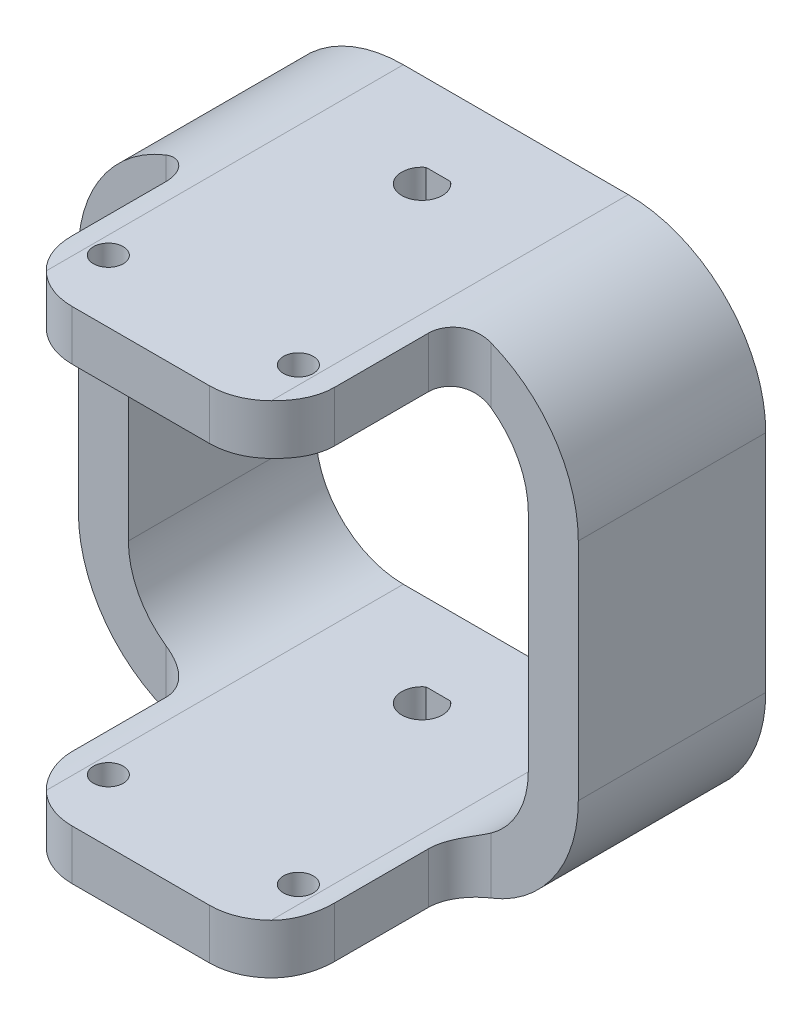
SolidWorks part; units mm, degrees
material "Plastique personnalisé"
ref_plane "Plan de face" through (0, 0, 0) normal (0, 0, 1) x (1, 0, 0)
ref_plane "Plan de dessus" through (0, 0, 0) normal (0, 1, 0) x (1, 0, 0)
ref_plane "Plan de droite" through (0, 0, 0) normal (1, 0, 0) x (0, 0, -1)
sketch "Esquisse1" plane through (0, 0, 0) normal (0, 0, 1) x (1, 0, 0)
  line L1 (40, -40) -> (-40, -40)
  line L2 (40, -40) -> (40, 40)
  line L3 (40, 40) -> (-40, 40)
  line L4 (-40, -40) -> (-40, 40)
  line L5 (40, -40) -> (-40, 40) construction
  line L6 (40, 40) -> (-40, -40) construction
  line L7 (-32, -32) -> (32, -32)
  line L8 (-32, -32) -> (-32, 32)
  line L9 (-32, 32) -> (32, 32)
  line L10 (32, -32) -> (32, 32)
  line L11 (-32, -32) -> (32, 32) construction
  line L12 (-32, 32) -> (32, -32) construction
  point P0 (0, 0)
  point P11 (0, 0)
  dimension "D1" = 8
  dimension "D3" = 80
extrude "Boss.-Extru.1" add sketch "Esquisse1" along normal mid plane 30
sketch "Esquisse2" plane through (0, 0, 0) normal (1, 0, 0) x (0, 0, -1)
  circle A0 centre (0, 0) radius 5
  dimension "D1" = 10
extrude "Enlèv. mat.-Extru.1" [suppressed] cut sketch "Esquisse2" against normal through all both and the other way through all
sketch "Esquisse3" plane through (0, -40, 0) normal (0, -1, 0) x (-1, 0, 0)
  circle A0 centre (0, 0) radius 5
  dimension "D1" = 10
extrude "Boss.-Extru.2" [suppressed] add sketch "Esquisse3" along normal blind 20
mirror "Symétrie1" [suppressed] about plane through (0, 0, 0) normal (0, 1, 0)
sketch "Esquisse7" plane through (0, 0, 15) normal (0, 0, 1) x (1, 0, 0)
  line L0 (40, 40) -> (-40, 40) construction
  line L1 (21, 32) -> (-21, 32)
  line L2 (21, 32) -> (21, 40)
  line L3 (21, 40) -> (-21, 40)
  line L4 (-21, 32) -> (-21, 40)
  line L5 (40, 40) -> (-40, 40) construction
  line L6 (32, 32) -> (-32, 32) construction
  point P10 (0, 40)
  point P11 (0, 40)
  dimension "D1" = 42
extrude "Boss.-Extru.4" add sketch "Esquisse7" along normal blind 30
sketch "Esquisse5" [suppressed] plane through (0, -60, 0) normal (0, -1, 0) x (1, 0, 0)
  circle A0 centre (0, 0) radius 3
  circle A1 centre (0, 0) radius 5 construction
  dimension "D1" = 6
extrude "Boss.-Extru.3" [suppressed] add sketch "Esquisse5" along normal blind 15
sketch "Esquisse6" [suppressed] plane through (0, -75, 0) normal (0, -1, 0) x (1, 0, 0)
  line L1 (3, -3) -> (-3, -3)
  line L2 (3, -3) -> (3, -1.8)
  line L3 (3, -1.8) -> (-3, -1.8)
  line L4 (-3, -3) -> (-3, -1.8)
  circle A0 centre (0, 0) radius 3 construction
  dimension "D1" = 1.2
extrude "Enlèv. mat.-Extru.2" [suppressed] cut sketch "Esquisse6" against normal up to surface (15 mm away) contours L1 L4 L3 L2
hole_wizard "Perçage pour écrous auto-bloquants 300® #6 (SP)1" positions "Esquisse10" profile "Esquisse9" hole size "#6-32" standard "PEM® Inch" end condition through all
sketch "Esquisse10" plane through (0, 40, 0) normal (0, -1, 0) x (0, 0, -1)
  line L0 (-35, 15.205) -> (-35, -15.205) construction
  line L3 (-35, 0) -> (-45, 0) construction
  line L6 (-45, 21) -> (-45, -21) construction
  point P0 (-35, 15.205)
  point P2 (-35, -15.205)
  point P20 (-45, 0)
  dimension "D1" = 30.41
  dimension "D2" = 10
sketch "Esquisse9" plane through (15.205, 40, 35) normal (1, 0, 0) x (0, 0, 1)
  line L0 (0, 0) -> (0, 80)
  line L1 (0, 80) -> (2.3812, 80)
  line L2 (2.3812, 80) -> (2.3812, 0)
  line L5 (2.3812, 0) -> (0, 0)
  line L11 (0, -6.35) -> (0, 107.95) construction
  dimension "Diamètre du perçage jusqu'au prochain" = 4.7625
  dimension "Profondeur du perçage jusqu'au prochain" = 80
fillet "Congé1" radius 10 2 edges at (21, 36, 45) (-21, 36, 45)
mirror "Symétrie2" about plane through (0, 0, 0) normal (0, 1, 0) of "Boss.-Extru.4", "Perçage pour écrous auto-bloquants 300® #6 (SP)1", "Congé1"
fillet "Congé2" radius 22 4 edges at (40, -40, 0) (-40, -40, 0) (-40, 40, 0) (40, 40, 0)
fillet "Congé3" radius 14 4 edges at (-32, 32, 0) (-32, -32, 0) (32, -32, 0) (32, 32, 0)
fillet "Congé4" radius 5 4 edges at (-21, -35.7346, 15) (-21, 35.7346, 15) (21, -35.7346, 15) (21, 35.7346, 15)
sketch "Esquisse11" plane through (0, -40, -40) normal (0, 1, 0) x (1, 0, 0)
  line L0 (40, -40) -> (-40, -40) construction
  line L1 (40, -25) -> (40, -55) construction
  line L2 (-40, -55) -> (-40, -25) construction
  line L3 (1.9649, -37.405) -> (-1.9649, -37.405)
  arc A0 (-1.9649, -37.405) -> (1.9649, -37.405) centre (0, -40) ccw
  dimension "D1" = 6.51
  dimension "D2" = 5.85
extrude "Enlèv. mat.-Extru.3" cut sketch "Esquisse11" along normal through all
